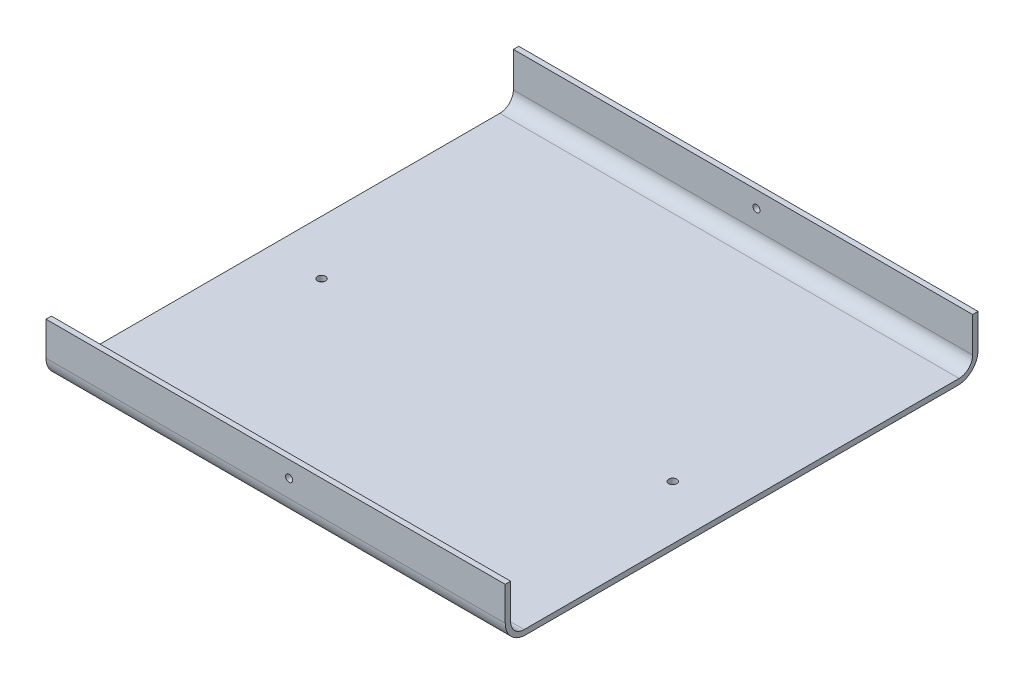
SolidWorks part; units mm, degrees
ref_plane "Front Plane" through (0, 0, 0) normal (0, 0, 1) x (1, 0, 0)
ref_plane "Top Plane" through (0, 0, 0) normal (0, 1, 0) x (1, 0, 0)
ref_plane "Right Plane" through (0, 0, 0) normal (1, 0, 0) x (0, 0, -1)
sketch "Sketch2" plane through (0, 0, 0) normal (1, 0, 0) x (0, 0, -1)
  line L0 (-80, 0) -> (80, 0)
  line L1 (87.5, 7.5) -> (87.5, 20)
  line L2 (87.5, 20) -> (85.5, 20)
  line L3 (85.5, 20) -> (85.5, 7)
  line L6 (0, -0.0495) -> (0, 0) construction
  line L8 (-85.5, 20) -> (-85.5, 7)
  line L9 (-87.5, 20) -> (-85.5, 20)
  line L10 (-87.5, 7.5) -> (-87.5, 20)
  line L12 (-80.5, 2) -> (80.5, 2)
  arc A0 (80, 0) -> (87.5, 7.5) centre (80, 7.5) ccw
  arc A1 (85.5, 7) -> (80.5, 2) centre (80.5, 7) cw
  arc A2 (-85.5, 7) -> (-80.5, 2) centre (-80.5, 7) ccw
  arc A3 (-80, 0) -> (-87.5, 7.5) centre (-80, 7.5) cw
  point P24 (0, 0)
  dimension "D1" = 7.5
  dimension "D2" = 5
  dimension "D5" = 160
  dimension "D3" = 2
  dimension "D4" = 161
  dimension "D6" = 12.5
  dimension "D7" = 2
extrude "Boss-Extrude1" add sketch "Sketch2" along normal blind 170
sketch "Sketch3" plane through (0, 2, 0) normal (0, 1, 0) x (1, 0, 0)
  line L0 (85, 80.5) -> (85, -80.5) construction
  line L1 (170, 80.5) -> (0, 80.5) construction
  line L2 (170, -80.5) -> (0, -80.5) construction
  circle A0 centre (20, -5.5) radius 1.5
  circle A1 centre (150, -5.5) radius 1.5
  dimension "D1" = 3
  dimension "D2" = 65
  dimension "D3" = 75
extrude "Cut-Extrude2" cut sketch "Sketch3" against normal blind 170
sketch "Sketch4" plane through (0, 0, 87.5) normal (0, 0, 1) x (1, 0, 0)
  line L0 (85, 20) -> (85, 7.5) construction
  line L1 (170, 20) -> (0, 20) construction
  line L2 (170, 7.5) -> (0, 7.5) construction
  line L3 (85, 14) -> (90, 14)
  line L4 (75, 19) -> (95, 19)
  line L5 (75, 19) -> (75, 9)
  line L6 (75, 9) -> (95, 9)
  line L7 (95, 19) -> (95, 9)
  line L8 (75, 19) -> (95, 9) construction
  line L9 (75, 9) -> (95, 19) construction
  circle A1 centre (90, 14) radius 1.3
  point P6 (85, 14)
  dimension "D5" = 2.6
  dimension "D1" = 20
  dimension "D2" = 10
  dimension "D3" = 1
  dimension "D4" = 5
extrude "Cut-Extrude3" cut sketch "Sketch4" against normal blind 200
